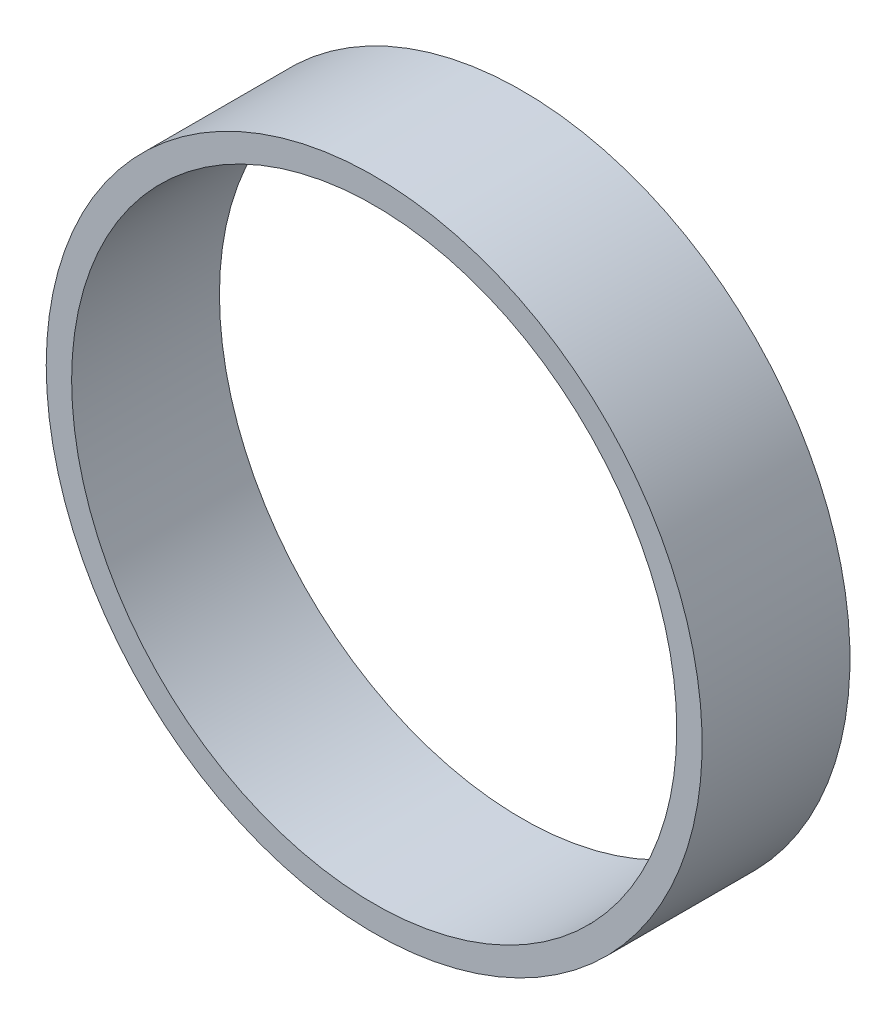
SolidWorks part; units mm, degrees
ref_plane "Front Plane" through (0, 0, 0) normal (0, 0, 1) x (1, 0, 0)
ref_plane "Top Plane" through (0, 0, 0) normal (0, 1, 0) x (1, 0, 0)
ref_plane "Right Plane" through (0, 0, 0) normal (1, 0, 0) x (0, 0, -1)
sketch "Sketch1" plane through (0, 0, 0) normal (0, 1, 0) x (1, 0, 0)
  line L0 (-91.9441, 0) -> (102.1149, 0) construction
  line L1 (0, 72.6196) -> (0, -82.7904) construction
  line L3 (-71, 16) -> (-65.5, 16)
  line L4 (-71, 16) -> (-71, -16)
  line L5 (-71, -16) -> (-65.5, -16)
  line L6 (-65.5, 16) -> (-65.5, -16)
  point P5 (-68.25, 0)
  dimension "D1" = 65.5
  dimension "D2" = 32
  dimension "D3" = 71
revolve "Revolve2" add sketch "Sketch1" angle 360 about L1
